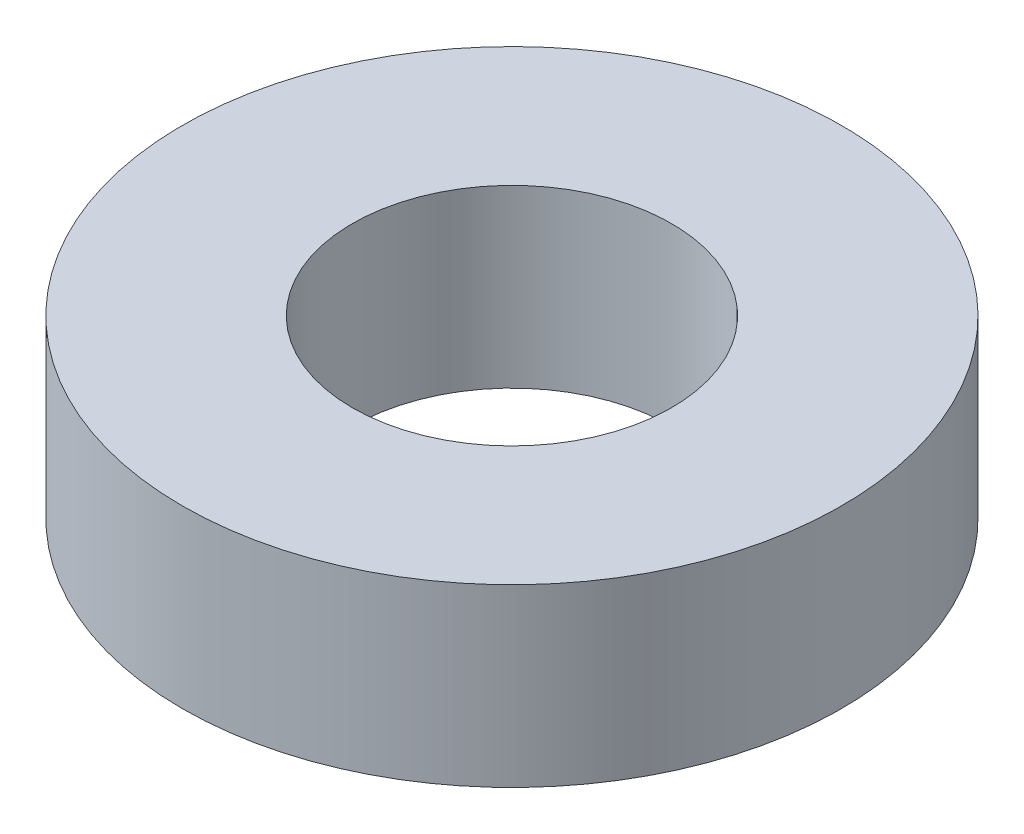
SolidWorks part; units mm, degrees
ref_plane "Front Plane" through (0, 0, 0) normal (0, 0, 1) x (1, 0, 0)
ref_plane "Top Plane" through (0, 0, 0) normal (0, 1, 0) x (1, 0, 0)
ref_plane "Right Plane" through (0, 0, 0) normal (1, 0, 0) x (0, 0, -1)
sketch "Sketch1" plane through (0, 0, 0) normal (0, 1, 0) x (1, 0, 0)
  circle A0 centre (0, 0) radius 23.46
  circle A1 centre (0, 0) radius 11.36
  dimension "D1" = 12.1
  dimension "D2" = 46.92
extrude "Boss-Extrude1" add sketch "Sketch1" along normal blind 12.5
